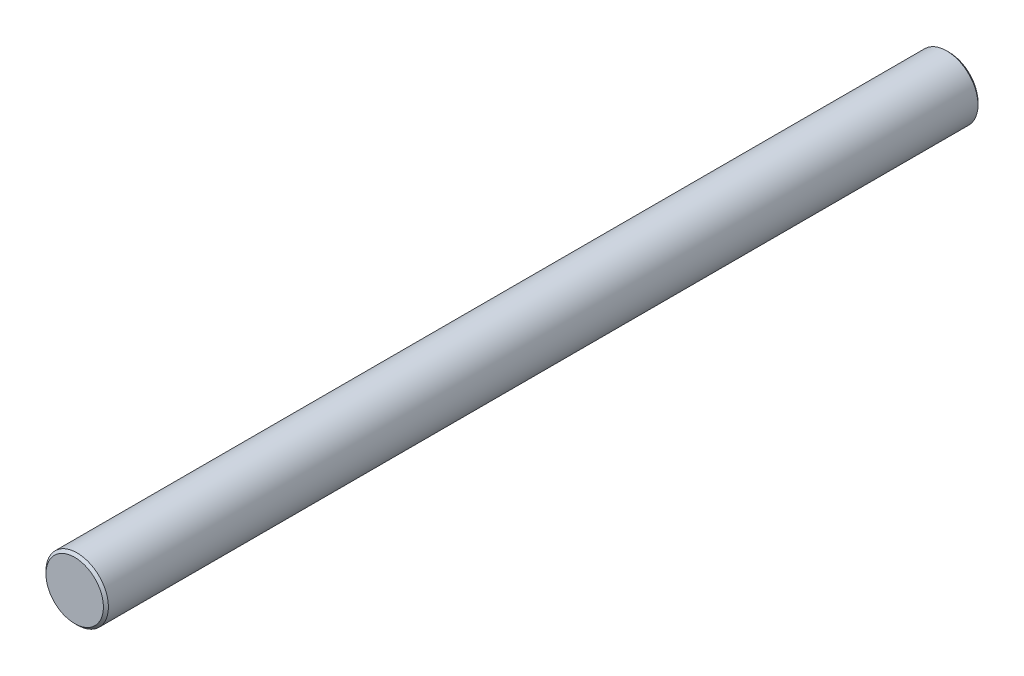
SolidWorks part; units mm, degrees
ref_plane "Спереди" through (0, 0, 0) normal (0, 0, 1) x (1, 0, 0)
ref_plane "Сверху" through (0, 0, 0) normal (0, 1, 0) x (1, 0, 0)
ref_plane "Справа" through (0, 0, 0) normal (1, 0, 0) x (0, 0, -1)
sketch "Эскиз1" plane through (0, 0, 0) normal (0, 0, 1) x (1, 0, 0)
  circle A0 centre (0, 0) radius 2.5
  dimension "D1" = 5
extrude "Бобышка-Вытянуть1" add sketch "Эскиз1" along normal blind 70
chamfer "Фаска1" distance 0.2 angle 45 2 edges at (2.5, 0, 0) (2.5, 0, 70)
